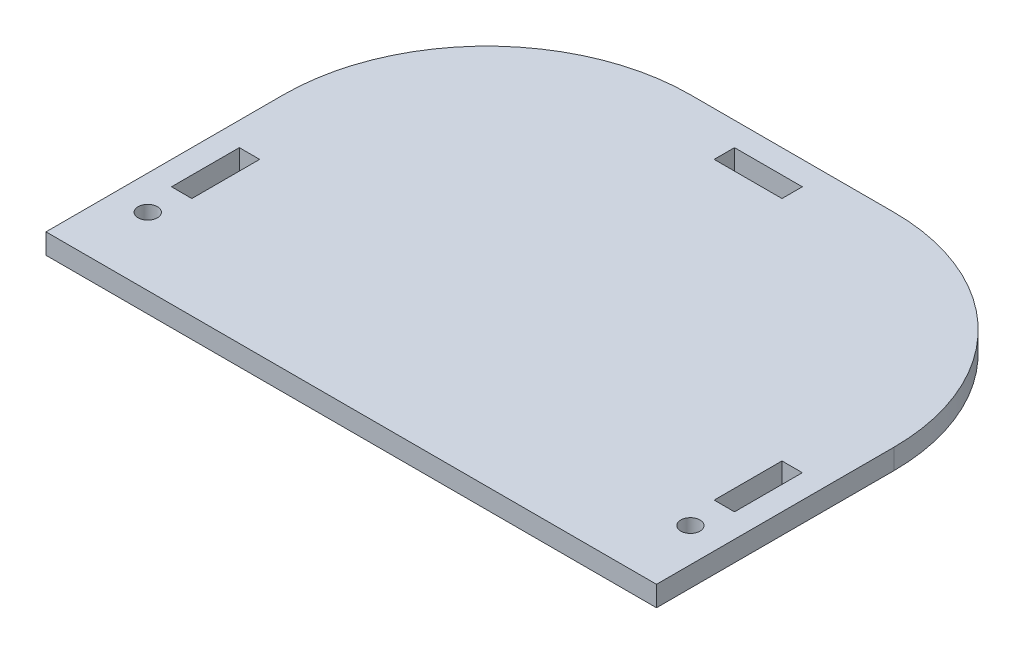
SolidWorks part; units mm, degrees
ref_plane "Front Plane" through (0, 0, 0) normal (0, 0, 1) x (1, 0, 0)
ref_plane "Top Plane" through (0, 0, 0) normal (0, 1, 0) x (1, 0, 0)
ref_plane "Right Plane" through (0, 0, 0) normal (1, 0, 0) x (0, 0, -1)
sketch "Sketch1" plane through (0, 0, 0) normal (0, 1, 0) x (1, 0, 0)
  line L1 (-40, 55) -> (40, 55) construction
  line L2 (-40, 55) -> (-40, 0) construction
  line L3 (-40, 0) -> (40, 0) construction
  line L4 (40, 55) -> (40, 0) construction
  line L5 (-5, 56.5) -> (5, 56.5)
  line L6 (-5, 56.5) -> (-5, 53.5)
  line L7 (-5, 53.5) -> (5, 53.5)
  line L8 (5, 56.5) -> (5, 53.5)
  line L9 (-41.5, 20) -> (-38.5, 20)
  line L10 (-41.5, 20) -> (-41.5, 10)
  line L11 (-41.5, 10) -> (-38.5, 10)
  line L12 (-38.5, 20) -> (-38.5, 10)
  line L13 (38.5, 20) -> (41.5, 20)
  line L14 (38.5, 20) -> (38.5, 10)
  line L15 (38.5, 10) -> (41.5, 10)
  line L16 (41.5, 20) -> (41.5, 10)
  line L17 (-45, 60) -> (45, 60)
  line L18 (-45, 60) -> (-45, -5)
  line L19 (-45, -5) -> (45, -5)
  line L20 (45, 60) -> (45, -5)
  circle A0 centre (-40, 5) radius 1.425
  circle A1 centre (40, 5) radius 1.425
  point P4 (0, 0)
  point P18 (0, 56.5)
  point P19 (0, 55)
  point P20 (-5, 55)
  point P21 (41.5, 15)
  point P23 (40, 10)
  point P24 (-41.5, 15)
  point P26 (-40, 20)
  point P31 (0, -5)
  dimension "D9" = 2.85
  dimension "D10" = 2.85
  dimension "D12" = 15
  dimension "D13" = 5
  dimension "D1" = 80
  dimension "D2" = 55
  dimension "D3" = 10
  dimension "D4" = 3
  dimension "D5" = 10
  dimension "D6" = 3
  dimension "D7" = 10
  dimension "D8" = 3
  dimension "D11" = 15
  dimension "D14" = 5
  dimension "D15" = 5
  dimension "D16" = 90
  dimension "D17" = 65
extrude "Boss-Extrude1" add sketch "Sketch1" along normal blind 3 contours L17 L20 L19 L18
fillet "Fillet1" radius 30 2 edges at (45, 1.5, -60) (-45, 1.5, -60)
